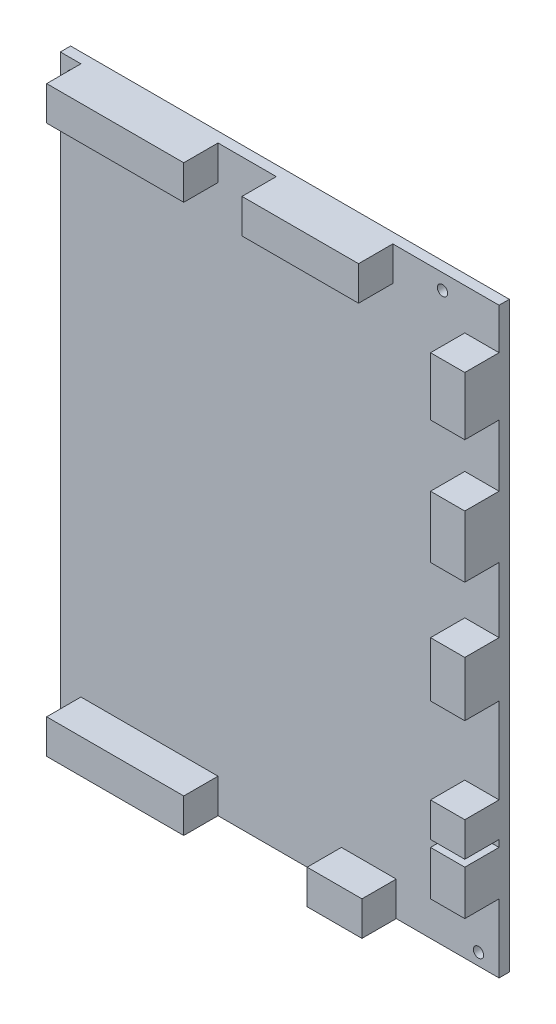
SolidWorks part; units mm, degrees
material "ABS PC"
ref_plane "前基準面" through (0, 0, 0) normal (0, 0, 1) x (1, 0, 0)
ref_plane "上基準面" through (0, 0, 0) normal (0, 1, 0) x (1, 0, 0)
ref_plane "右基準面" through (0, 0, 0) normal (1, 0, 0) x (0, 0, -1)
sketch "草圖1" plane through (0, 0, 0) normal (0, 0, 1) x (1, 0, 0)
  line L1 (-48.9819, 53.3718) -> (79.0181, 53.3718)
  line L2 (-48.9819, 53.3718) -> (-48.9819, -116.6282)
  line L3 (-48.9819, -116.6282) -> (79.0181, -116.6282)
  line L4 (79.0181, 53.3718) -> (79.0181, -116.6282)
  circle A0 centre (-45.4819, 48.8718) radius 1.5
  circle A1 centre (-45.4819, -112.1282) radius 1.5
  circle A2 centre (73.0181, -113.1282) radius 1.5
  circle A3 centre (62.5181, 48.8718) radius 1.5
  dimension "D3" = 3
  dimension "D4" = 3
  dimension "D5" = 4.5
  dimension "D7" = 3.5
  dimension "D9" = 3
  dimension "D10" = 3.5
  dimension "D14" = 3
  dimension "D1" = 128
  dimension "D2" = 170
  dimension "D6" = 161
  dimension "D8" = 3.5
  dimension "D11" = 6
  dimension "D12" = 16.5
  dimension "D13" = 4.5
extrude "填料-伸長1" add sketch "草圖1" along normal blind 3
sketch "草圖2" plane through (0, 0, 3) normal (0, 0, 1) x (1, 0, 0)
  line L0 (-48.9819, -116.6282) -> (79.0181, -116.6282) construction
  line L1 (-42.9819, -116.6282) -> (-2.9819, -116.6282)
  line L2 (-42.9819, -116.6282) -> (-42.9819, -106.6282)
  line L3 (-42.9819, -106.6282) -> (-2.9819, -106.6282)
  line L4 (-2.9819, -116.6282) -> (-2.9819, -106.6282)
  line L5 (-48.9819, 53.3718) -> (-48.9819, -116.6282) construction
  line L6 (79.0181, -116.6282) -> (79.0181, 53.3718) construction
  line L7 (49.0181, -116.6282) -> (33.0181, -116.6282)
  line L8 (49.0181, -116.6282) -> (49.0181, -106.6282)
  line L9 (49.0181, -106.6282) -> (33.0181, -106.6282)
  line L10 (33.0181, -116.6282) -> (33.0181, -106.6282)
  line L11 (79.0181, 53.3718) -> (-48.9819, 53.3718) construction
  line L12 (79.0181, -96.6282) -> (69.0181, -96.6282)
  line L13 (79.0181, -96.6282) -> (79.0181, -83.6282)
  line L14 (79.0181, -83.6282) -> (69.0181, -83.6282)
  line L15 (69.0181, -96.6282) -> (69.0181, -83.6282)
  line L16 (79.0181, -81.6282) -> (69.0181, -81.6282)
  line L17 (79.0181, -81.6282) -> (79.0181, -71.6282)
  line L18 (79.0181, -71.6282) -> (69.0181, -71.6282)
  line L19 (69.0181, -81.6282) -> (69.0181, -71.6282)
  line L20 (79.0181, -46.6282) -> (69.0181, -46.6282)
  line L21 (79.0181, -46.6282) -> (79.0181, -30.6282)
  line L22 (79.0181, -30.6282) -> (69.0181, -30.6282)
  line L23 (69.0181, -46.6282) -> (69.0181, -30.6282)
  line L24 (79.0181, -11.6282) -> (69.0181, -11.6282)
  line L25 (79.0181, -11.6282) -> (79.0181, 6.3718)
  line L26 (79.0181, 6.3718) -> (69.0181, 6.3718)
  line L27 (69.0181, -11.6282) -> (69.0181, 6.3718)
  line L28 (79.0181, 24.3718) -> (69.0181, 24.3718)
  line L29 (79.0181, 24.3718) -> (79.0181, 41.3718)
  line L30 (79.0181, 41.3718) -> (69.0181, 41.3718)
  line L31 (69.0181, 24.3718) -> (69.0181, 41.3718)
  line L33 (14.0181, 53.3718) -> (48.0181, 53.3718)
  line L34 (14.0181, 53.3718) -> (14.0181, 43.3718)
  line L35 (14.0181, 43.3718) -> (48.0181, 43.3718)
  line L36 (48.0181, 53.3718) -> (48.0181, 43.3718)
  line L37 (-42.9819, 53.3718) -> (-2.9819, 53.3718)
  line L38 (-42.9819, 53.3718) -> (-42.9819, 43.3718)
  line L39 (-42.9819, 43.3718) -> (-2.9819, 43.3718)
  line L40 (-2.9819, 53.3718) -> (-2.9819, 43.3718)
  point P36 (74.0181, -11.6282)
  dimension "D1" = 6
  dimension "D2" = 10
  dimension "D3" = 46
  dimension "D4" = 30
  dimension "D5" = 10
  dimension "D6" = 46
  dimension "D7" = 10
  dimension "D8" = 20
  dimension "D9" = 33
  dimension "D10" = 10
  dimension "D11" = 35
  dimension "D12" = 45
  dimension "D13" = 10
  dimension "D14" = 70
  dimension "D15" = 86
  dimension "D16" = 12
  dimension "D17" = 29
  dimension "D18" = 10
  dimension "D19" = 10
  dimension "D20" = 47
  dimension "D21" = 65
  dimension "D22" = 10
  dimension "D23" = 31
  dimension "D24" = 65
  dimension "D25" = 6
  dimension "D26" = 46
  dimension "D27" = 10
extrude "填料-伸長2" add sketch "草圖2" along normal blind 10
